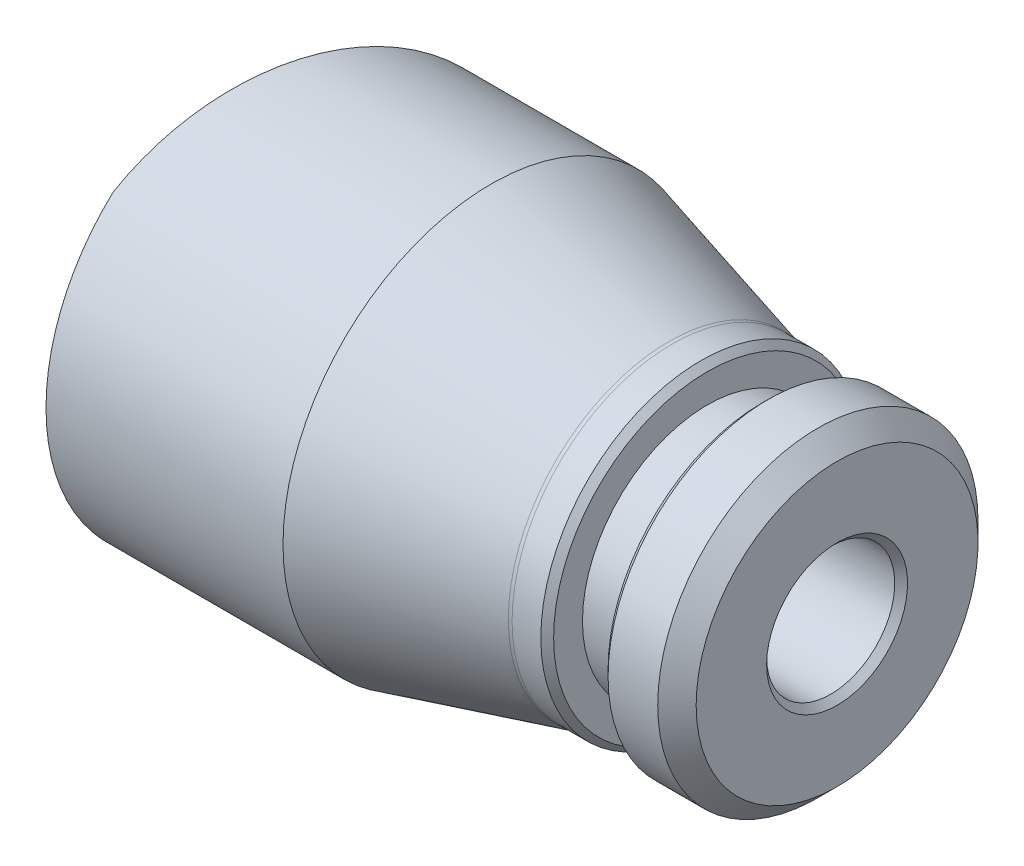
SolidWorks part; units mm, degrees
ref_plane "Спереди" through (0, 0, 0) normal (0, 0, 1) x (1, 0, 0)
ref_plane "Сверху" through (0, 0, 0) normal (0, 1, 0) x (1, 0, 0)
ref_plane "Справа" through (0, 0, 0) normal (1, 0, 0) x (0, 0, -1)
other "Configuration Table"
sketch "Эскиз1" plane through (0, 0, 0) normal (0, 0, 1) x (1, 0, 0)
  line L0 (0, 32.5) -> (37, 32.5)
  line L1 (37, 32.5) -> (64.7457, 25.0681)
  line L2 (65.2632, 25) -> (69.75, 25)
  line L3 (69.75, 25) -> (70.75, 24)
  line L4 (70.75, 24) -> (70.75, 19.5)
  line L5 (70.75, 19.5) -> (79.25, 19.5)
  line L6 (79.25, 19.5) -> (79.25, 24)
  line L7 (79.25, 24) -> (80.25, 25)
  line L8 (80.25, 25) -> (88, 25)
  line L9 (88, 25) -> (91, 22)
  line L10 (91, 22) -> (91, 11)
  line L11 (91, 11) -> (90, 10)
  line L12 (90, 10) -> (61, 10)
  line L13 (61, 10) -> (61, 19)
  line L14 (60, 20) -> (25, 20)
  line L15 (25, 20) -> (25, 27.1)
  line L16 (24.6, 27.5) -> (0, 27.5)
  line L17 (0, 27.5) -> (0, 32.5)
  line L18 (0, 0) -> (100, 0) construction
  arc A0 (64.7457, 25.0681) -> (65.2632, 25) centre (65.2632, 27) ccw
  arc A1 (61, 19) -> (60, 20) centre (60, 19) ccw
  arc A2 (25, 27.1) -> (24.6, 27.5) centre (24.6, 27.1) ccw
revolve "Точеный профиль" add sketch "Эскиз1" angle 360 about L18
sketch "Эскиз2" plane through (0, 0, 0) normal (0, 1, 0) x (1, 0, 0)
  line L0 (-25, 50) -> (15.3041, 50)
  line L1 (15.3041, 50) -> (-5.9516, -50)
  line L2 (-5.9516, -50) -> (-25, -50)
  line L3 (-25, -50) -> (-25, 50)
extrude "Наклон торца 12 градусов" cut sketch "Эскиз2" against normal through all and the other way through all
sketch "Эскиз3" plane through (0, 0, 0) normal (1, 0, 0) x (0, 0, -1)
  line L0 (0, -2.5) -> (0, 2.5)
  line L1 (0, 2.5) -> (-12.05, 2.5)
  line L2 (-12.3, 2.25) -> (-12.3, -2.25)
  line L3 (-12.05, -2.5) -> (0, -2.5)
  arc A0 (-12.05, 2.5) -> (-12.3, 2.25) centre (-12.05, 2.25) ccw
  arc A1 (-12.3, -2.25) -> (-12.05, -2.5) centre (-12.05, -2.25) ccw
